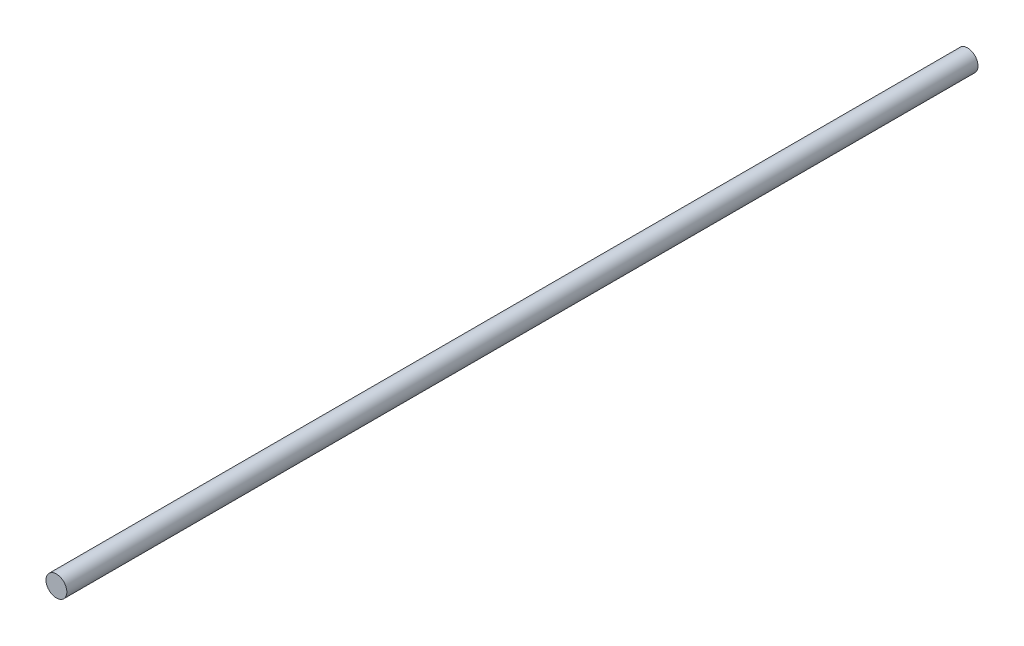
SolidWorks part; units mm, degrees
material "AISI 4130 Steel, annealed at 865C"
ref_plane "Front Plane" through (0, 0, 0) normal (0, 0, 1) x (1, 0, 0)
ref_plane "Top Plane" through (0, 0, 0) normal (0, 1, 0) x (1, 0, 0)
ref_plane "Right Plane" through (0, 0, 0) normal (1, 0, 0) x (0, 0, -1)
sketch "Sketch1" plane through (0, 0, 0) normal (0, 0, 1) x (1, 0, 0)
  circle A0 centre (0, 0) radius 12.7
  dimension "D1" = 25.4
extrude "Boss-Extrude1" add sketch "Sketch1" along normal blind 1110
